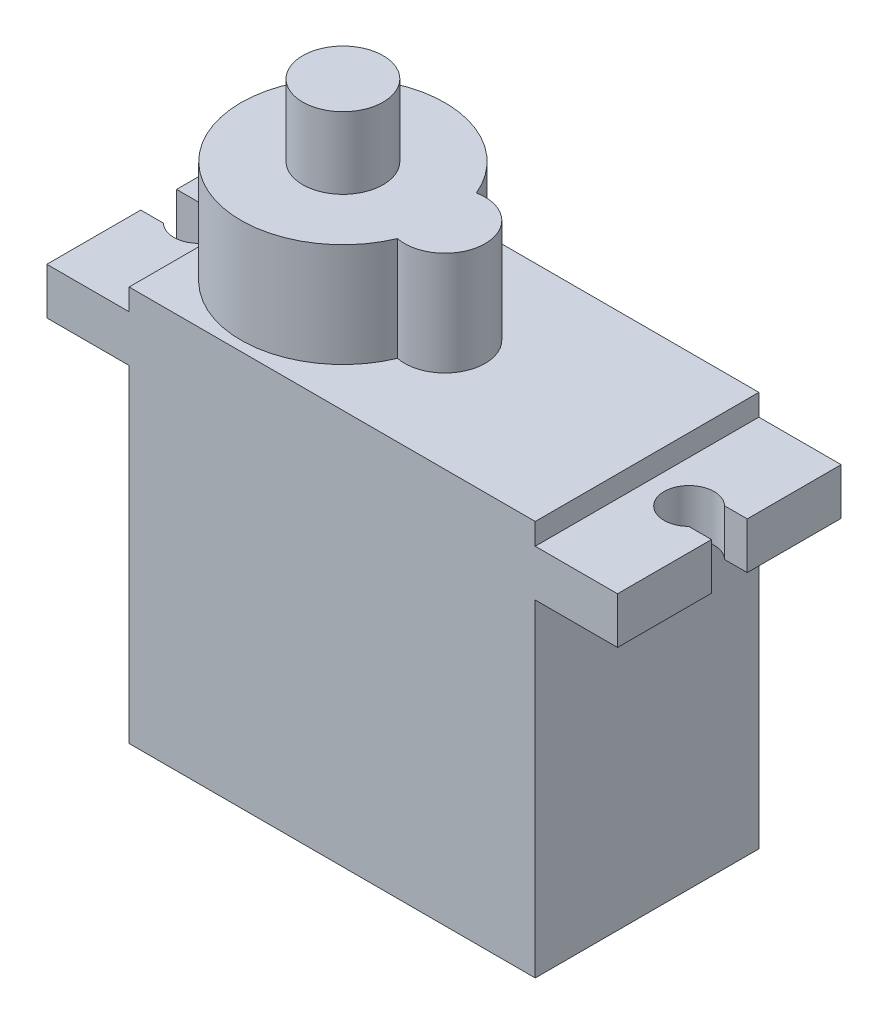
SolidWorks part; units mm, degrees
material "ABS"
ref_plane "Plano frontal" through (0, 0, 0) normal (0, 0, 1) x (1, 0, 0)
ref_plane "Plano superior" through (0, 0, 0) normal (0, 1, 0) x (1, 0, 0)
ref_plane "Plano direito" through (0, 0, 0) normal (1, 0, 0) x (0, 0, -1)
sketch "Esboço1" plane through (0, 0, 0) normal (0, 0, 1) x (1, 0, 0)
  line L0 (0, 0) -> (0, 20.9) construction
  line L1 (11.35, 11.75) -> (15.95, 11.75)
  line L2 (-11.35, 9.15) -> (-11.35, -9.15)
  line L3 (-11.35, -9.15) -> (11.35, -9.15)
  line L4 (11.35, 9.15) -> (11.35, -9.15)
  line L5 (-11.35, 9.15) -> (11.35, -9.15) construction
  line L6 (-11.35, -9.15) -> (11.35, 9.15) construction
  line L7 (11.35, 9.15) -> (15.95, 9.15)
  line L8 (-15.95, 11.75) -> (-11.35, 11.75)
  line L9 (-15.95, 11.75) -> (-15.95, 9.15)
  line L10 (-15.95, 9.15) -> (-11.35, 9.15)
  line L11 (15.95, 11.75) -> (15.95, 9.15)
  line L12 (-15.95, 11.75) -> (15.95, 9.15) construction
  line L13 (-15.95, 9.15) -> (15.95, 11.75) construction
  line L14 (-11.35, 12.95) -> (11.35, 12.95)
  line L15 (-11.35, 12.95) -> (-11.35, 11.75)
  line L17 (11.35, 12.95) -> (11.35, 11.75)
  line L18 (-11.35, 12.95) -> (11.35, 11.75) construction
  line L19 (-11.35, 11.75) -> (11.35, 12.95) construction
  point P0 (0, 0)
  point P8 (0, 10.45)
  point P13 (0, 12.35)
  dimension "D1" = 22.1
  dimension "D2" = 22.7
  dimension "D3" = 4.6
  dimension "D4" = 1.2
  dimension "D5" = 2.6
extrude "Ressalto-extrusão1" add sketch "Esboço1" along normal blind 12.5
sketch "Esboço2" plane through (0, 12.95, 0) normal (0, 1, 0) x (1, 0, 0)
  line L0 (-5.65, -6.25) -> (-11.35, -6.25) construction
  line L2 (-11.35, -12.5) -> (-11.35, 0) construction
  arc A0 (-0.3941, -4.0443) -> (-0.3941, -8.4557) centre (-5.65, -6.25) ccw
  arc A1 (-0.3941, -8.4557) -> (-0.3941, -4.0443) centre (0.05, -6.25) ccw
  dimension "D1" = 5.7
  dimension "D3" = 5.7
  dimension "D4" = 2.25
  dimension "D2" = 5.7
extrude "Ressalto-extrusão2" add sketch "Esboço2" along normal blind 5.8
sketch "Esboço3" plane through (0, 11.75, 0) normal (0, 1, 0) x (1, 0, 0)
  line L0 (-15.95, -6.25) -> (-13.7, -6.25) construction
  line L1 (-15.95, -12.5) -> (-15.95, 0) construction
  line L2 (-15.95, -7.25) -> (-14.6798, -7.25)
  line L3 (-15.95, -5.25) -> (-14.6798, -5.25)
  line L4 (-15.95, -5.25) -> (-15.95, -7.25)
  line L5 (-15.95, -7.25) -> (-13.7, -7.25) construction
  line L6 (-15.95, -5.25) -> (-13.7, -5.25) construction
  line L7 (0, 0) -> (0, -16.2082) construction
  line L8 (15.95, -6.25) -> (13.7, -6.25) construction
  line L9 (15.95, -5.25) -> (15.95, -7.25)
  line L10 (15.95, -5.25) -> (14.6798, -5.25)
  line L11 (15.95, -7.25) -> (14.6798, -7.25)
  arc A0 (-14.6798, -7.25) -> (-14.6798, -5.25) centre (-13.7, -6.25) ccw
  arc A1 (14.6798, -7.25) -> (14.6798, -5.25) centre (13.7, -6.25) cw
  dimension "D1" = 1
  dimension "D2" = 1
extrude "Corte-extrusão1" cut sketch "Esboço3" against normal blind 5.5
sketch "Esboço4" plane through (0, 18.75, 0) normal (0, 1, 0) x (1, 0, 0)
  circle A0 centre (-5.65, -6.25) radius 2.25
extrude "Ressalto-extrusão3" add sketch "Esboço4" along normal blind 4
